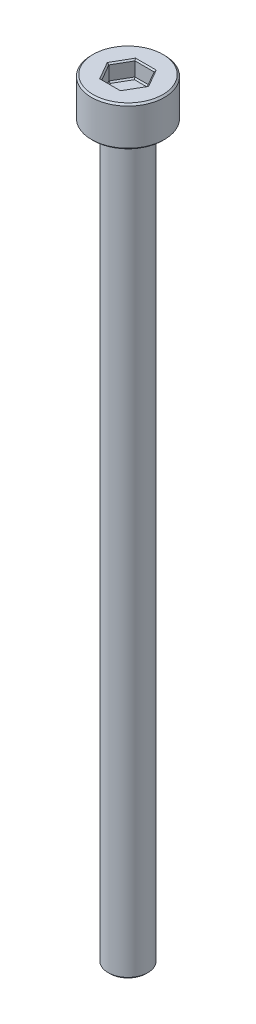
SolidWorks part; units mm, degrees
ref_plane "Front Plane" through (0, 0, 0) normal (0, 0, 1) x (1, 0, 0)
ref_plane "Top Plane" through (0, 0, 0) normal (0, 1, 0) x (1, 0, 0)
ref_plane "Right Plane" through (0, 0, 0) normal (1, 0, 0) x (0, 0, -1)
sketch "Sketch1" plane through (0, 0, 0) normal (0, 1, 0) x (1, 0, 0)
  circle A0 centre (0, 0) radius 2.75
  dimension "D1" = 5.5
extrude "Boss-Extrude1" add sketch "Sketch1" along normal blind 3
sketch "Sketch2" plane through (0, 0, 0) normal (0, -1, 0) x (-1, 0, 0)
  circle A0 centre (0, 0) radius 1.5
  dimension "D1" = 3
extrude "Boss-Extrude2" add sketch "Sketch2" along normal blind 55
chamfer "Chamfer1" distance 0.125 angle 45 2 edges at (0, 0, 2.75) (0, 3, 2.75)
chamfer "Chamfer2" distance 0.125 angle 45 1 edges at (0, -55, -1.5)
sketch "Sketch3" plane through (0, 3, 0) normal (0, 1, 0) x (1, 0, 0)
  line L1 (1.4434, 0) -> (0.7217, 1.25)
  line L2 (0.7217, 1.25) -> (-0.7217, 1.25)
  line L3 (-0.7217, 1.25) -> (-1.4434, 0)
  line L4 (-1.4434, 0) -> (-0.7217, -1.25)
  line L5 (-0.7217, -1.25) -> (0.7217, -1.25)
  line L6 (0.7217, -1.25) -> (1.4434, 0)
  circle A0 centre (0, 0) radius 1.25 construction
extrude "Cut-Extrude1" cut sketch "Sketch3" against normal blind 1.25
chamfer "Chamfer3" distance 0.1 angle 45 6 edges at (0, 3, 1.25) (1.0825, 3, 0.625) (1.0825, 3, -0.625) (-1.0825, 3, 0.625) (-1.0825, 3, -0.625) (0, 3, -1.25)
chamfer "Chamfer4" distance 0.1 angle 45 6 edges at (0, 1.75, 1.25) (1.0825, 1.75, 0.625) (1.0825, 1.75, -0.625) (-1.0825, 1.75, 0.625) (-1.0825, 1.75, -0.625) (0, 1.75, -1.25)
